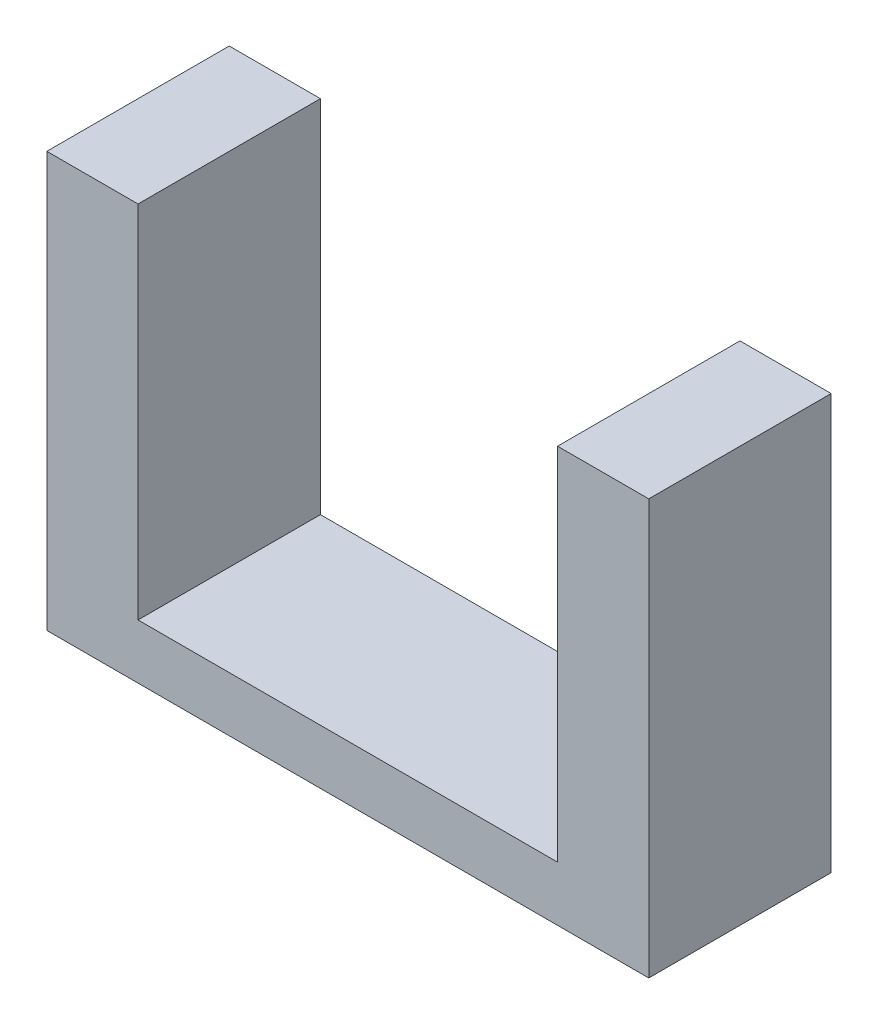
SolidWorks part; units mm, degrees
ref_plane "Front Plane" through (0, 0, 0) normal (0, 0, 1) x (1, 0, 0)
ref_plane "Top Plane" through (0, 0, 0) normal (0, 1, 0) x (1, 0, 0)
ref_plane "Right Plane" through (0, 0, 0) normal (1, 0, 0) x (0, 0, -1)
sketch "Sketch1" plane through (0, 0, 0) normal (0, 1, 0) x (1, 0, 0)
  line L0 (-16.5, 10) -> (-16.5, -10)
  line L1 (-11.5, 5) -> (11.5, 5)
  line L2 (-11.5, 5) -> (-11.5, -5)
  line L3 (-11.5, -5) -> (11.5, -5)
  line L4 (11.5, 5) -> (11.5, -5)
  line L5 (-11.5, 5) -> (11.5, -5) construction
  line L6 (-11.5, -5) -> (11.5, 5) construction
  line L7 (-16.5, -10) -> (16.5, -10)
  line L8 (16.5, 10) -> (16.5, -10)
  line L9 (-16.5, 10) -> (16.5, 10)
  line L10 (-11.5, 5) -> (-16.5, 5)
  line L11 (-11.5, 5) -> (-11.5, 10)
  line L12 (-11.5, -5) -> (-16.5, -5)
  line L13 (-11.5, -5) -> (-11.5, -10)
  line L14 (11.5, 5) -> (11.5, 10)
  line L15 (11.5, 5) -> (16.5, 5)
  line L16 (11.5, -10) -> (11.5, -5)
  line L17 (11.5, -5) -> (16.5, -5)
  point P0 (0, 0)
  dimension "D1" = 23
  dimension "D2" = 10
  dimension "D3" = 5
extrude "Boss-Extrude1" add sketch "Sketch1" along normal blind 3 contours L4 L1 L2 L3
sketch "Sketch2" plane through (0, 0, 0) normal (0, 1, 0) x (1, 0, 0)
  line L0 (16.5, 10) -> (16.5, -10) construction
  line L1 (11.5, -5) -> (16.5, -5) construction
  line L2 (11.5, 5) -> (16.5, 5) construction
  line L3 (11.5, 5) -> (11.5, -5) construction
  line L4 (-16.5, 10) -> (-16.5, -10) construction
  line L5 (-11.5, 5) -> (-11.5, -5) construction
  line L6 (-11.5, -5) -> (-16.5, -5) construction
  line L7 (-11.5, 5) -> (-16.5, 5) construction
  line L8 (16.5, 5) -> (16.5, -5)
  line L9 (11.5, -5) -> (16.5, -5)
  line L10 (11.5, 5) -> (16.5, 5)
  line L11 (11.5, 5) -> (11.5, -5)
  line L12 (-16.5, 5) -> (-16.5, -5)
  line L13 (-11.5, 5) -> (-11.5, -5)
  line L14 (-11.5, -5) -> (-16.5, -5)
  line L15 (-11.5, 5) -> (-16.5, 5)
extrude "Boss-Extrude2" add sketch "Sketch2" along normal blind 22.75
ref_plane "Plane1" through (0, 32.75, 0) normal (0, 1, 0) x (1, 0, 0)
